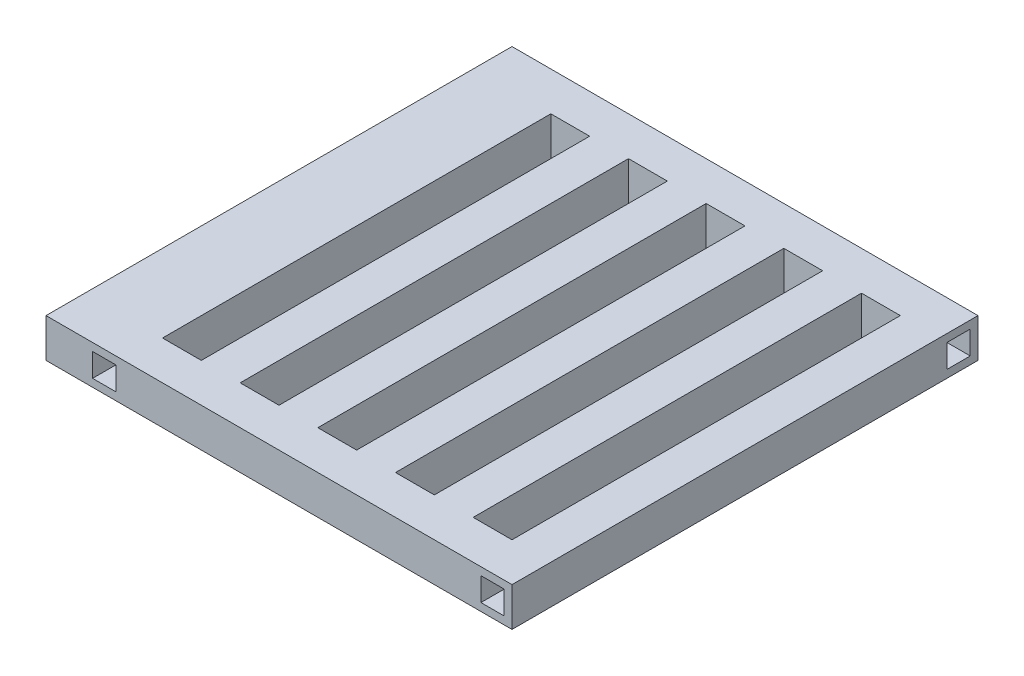
SolidWorks part; units mm, degrees
ref_plane "Front Plane" through (0, 0, 0) normal (0, 0, 1) x (1, 0, 0)
ref_plane "Top Plane" through (0, 0, 0) normal (0, 1, 0) x (1, 0, 0)
ref_plane "Right Plane" through (0, 0, 0) normal (1, 0, 0) x (0, 0, -1)
sketch "Sketch3" plane through (0, 0, 0) normal (0, 1, 0) x (1, 0, 0)
  line L1 (0, 0) -> (-152.4, 0)
  line L2 (0, 0) -> (0, 152.4)
  line L3 (0, 152.4) -> (-152.4, 152.4)
  line L4 (-152.4, 0) -> (-152.4, 152.4)
  dimension "D1" = 152.4
  dimension "D2" = 152.4
extrude "Boss-Extrude1" add sketch "Sketch3" along normal blind 12.7
sketch "Sketch5" plane through (-152.4, 0, 0) normal (-1, 0, 0) x (0, 0, 1)
  line L0 (-149.86, 2.54) -> (-149.86, 10.16)
  line L5 (-149.86, 10.16) -> (-2.54, 10.16)
  line L6 (-2.54, 2.54) -> (-2.54, 10.16)
  line L7 (-149.86, 2.54) -> (-2.54, 2.54)
extrude "Cut-Extrude1" cut sketch "Sketch5" against normal blind 12.7
sketch "Sketch6" plane through (0, 12.7, 0) normal (0, 1, 0) x (1, 0, 0)
  line L0 (-139.7, 12.7) -> (-139.7, 139.7)
  line L5 (-127, 12.7) -> (-127, 139.7)
  line L6 (-114.3, 12.7) -> (-114.3, 139.7)
  line L7 (-101.6, 12.7) -> (-101.6, 139.7)
  line L8 (-88.9, 12.7) -> (-88.9, 139.7)
  line L9 (-76.2, 12.7) -> (-76.2, 139.7)
  line L10 (-63.5, 12.7) -> (-63.5, 139.7)
  line L11 (-50.8, 12.7) -> (-50.8, 139.7)
  line L12 (-38.1, 12.7) -> (-38.1, 139.7)
  line L13 (-25.4, 12.7) -> (-25.4, 139.7)
  line L14 (-12.7, 12.7) -> (-12.7, 139.7)
  line L15 (-12.7, 12.7) -> (-12.7, 139.7)
  line L16 (-12.7, 139.7) -> (-139.7, 139.7)
  line L17 (-12.7, 12.7) -> (-139.7, 12.7)
  line L18 (-127, 0) -> (-127, 152.4) construction
  line L19 (-114.3, 0) -> (-114.3, 152.4) construction
  line L20 (-101.6, 0) -> (-101.6, 152.4) construction
  line L21 (-88.9, 0) -> (-88.9, 152.4) construction
  line L22 (-76.2, 0) -> (-76.2, 152.4) construction
  line L23 (-63.5, 0) -> (-63.5, 152.4) construction
  line L24 (-50.8, 0) -> (-50.8, 152.4) construction
  line L25 (-38.1, 0) -> (-38.1, 152.4) construction
  line L26 (-25.4, 0) -> (-25.4, 152.4) construction
  line L27 (-12.7, 0) -> (-12.7, 152.4) construction
  line L31 (-139.7, 0) -> (-139.7, 152.4) construction
  dimension "D1" = 12.7
  dimension "D2" = 12.7
  dimension "D3" = 12.7
  dimension "D4" = 12.7
  dimension "D5" = 12.7
  dimension "D6" = 12.7
  dimension "D7" = 12.7
  dimension "D8" = 12.7
  dimension "D9" = 12.7
  dimension "D10" = 12.7
extrude "Cut-Extrude3" cut sketch "Sketch6" against normal blind 12.7 contours L17 L6 L16 L5 | L17 L8 L16 L7 | L17 L10 L16 L9 | L17 L12 L16 L11 | L17 L14 L16 L13
sketch "Sketch7" plane through (0, 0, 0) normal (1, 0, 0) x (0, 0, -1)
  line L0 (0, 0) -> (152.4, 0) construction
  line L1 (0, 12.7) -> (12.7, 12.7)
  line L2 (0, 12.7) -> (0, 0)
  line L3 (0, 0) -> (12.7, 0)
  line L4 (12.7, 12.7) -> (12.7, 0)
  dimension "D1" = 12.7
sketch "Sketch8" plane through (0, 0, 0) normal (1, 0, 0) x (0, 0, -1)
  line L15 (149.86, 10.16) -> (142.24, 10.16)
  line L16 (142.24, 2.54) -> (142.24, 10.16)
  line L17 (149.86, 2.54) -> (142.24, 2.54)
  line L18 (149.86, 2.54) -> (149.86, 10.16)
  line L19 (2.54, 2.54) -> (10.16, 2.54)
  line L20 (2.54, 10.16) -> (2.54, 2.54)
  line L21 (10.16, 2.54) -> (10.16, 10.16)
  line L22 (10.16, 10.16) -> (2.54, 10.16)
  line L23 (2.54, 2.54) -> (10.16, 2.54)
  line L24 (2.54, 10.16) -> (2.54, 2.54)
  line L25 (10.16, 2.54) -> (10.16, 10.16)
  line L26 (10.16, 10.16) -> (2.54, 10.16)
  dimension "D2" = 2.54
extrude "Cut-Extrude4" cut sketch "Sketch8" against normal blind 25.4
sketch "Sketch9" plane through (0, 0, 0) normal (0, 0, 1) x (1, 0, 0)
  line L8 (-129.54, 10.16) -> (-129.54, 2.54)
  line L9 (-137.16, 2.54) -> (-129.54, 2.54)
  line L10 (-137.16, 10.16) -> (-137.16, 2.54)
  line L11 (-137.16, 10.16) -> (-129.54, 10.16)
extrude "Cut-Extrude5" cut sketch "Sketch9" against normal blind 25.4
sketch "Sketch10" plane through (0, 0, -152.4) normal (0, 0, -1) x (-1, 0, 0)
  line L11 (137.16, 2.54) -> (137.16, 10.16)
  line L12 (137.16, 10.16) -> (129.6511, 10.16)
  line L13 (129.6511, 2.54) -> (129.6511, 10.16)
  line L14 (137.16, 2.54) -> (129.6511, 2.54)
extrude "Cut-Extrude6" cut sketch "Sketch10" against normal blind 25.4
sketch "Sketch11" plane through (-25.4, 0, 0) normal (1, 0, 0) x (0, 0, -1)
  line L1 (2.54, 10.16) -> (10.16, 10.16)
  line L2 (2.54, 10.16) -> (2.54, 2.54)
  line L3 (2.54, 2.54) -> (10.16, 2.54)
  line L4 (10.16, 10.16) -> (10.16, 2.54)
extrude "Boss-Extrude3" add sketch "Sketch11" along normal blind 25.4
sketch "Sketch12" plane through (0, 0, 0) normal (0, 0, 1) x (1, 0, 0)
  line L5 (-10.16, 10.16) -> (-10.16, 2.54)
  line L6 (-2.54, 2.54) -> (-10.16, 2.54)
  line L7 (-2.54, 10.16) -> (-2.54, 2.54)
  line L8 (-2.54, 10.16) -> (-10.16, 10.16)
extrude "Cut-Extrude7" cut sketch "Sketch12" against normal blind 25.4
